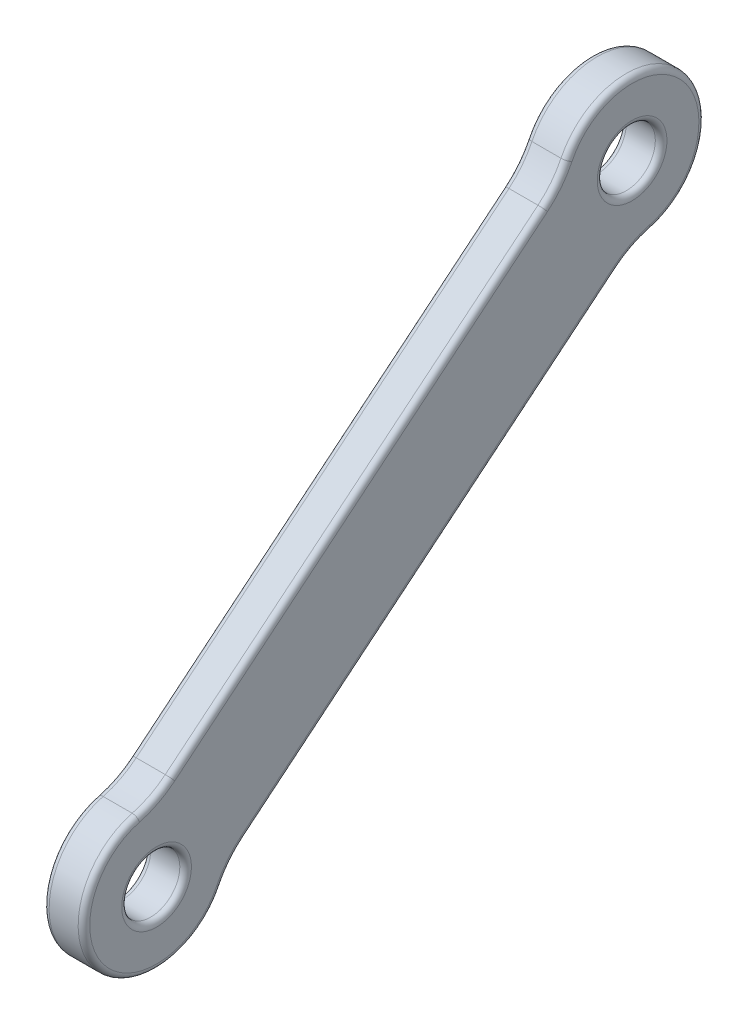
SolidWorks part; units mm, degrees
ref_plane "Front Plane" through (0, 0, 0) normal (1, 0, 0) x (0, 1, 0)
ref_plane "Top Plane" through (0, 0, 0) normal (0, 0, 1) x (0, 1, 0)
ref_plane "Right Plane" through (0, 0, 0) normal (0, 1, 0) x (-1, 0, 0)
sketch "Sketch1" plane through (0, 0, 0) normal (1, 0, 0) x (0, 1, 0)
  line L0 (-11.6048, -20) -> (24.9519, -20)
  line L1 (84.9519, 40) -> (84.9519, 57.8005)
  line L4 (-38.5328, 56.8878) -> (-47.7982, 43.6554)
  line L5 (64.9519, 37.5) -> (87.5414, -36.1119)
  line L6 (87.5414, -36.1119) -> (67.3498, -81.8536)
  line L7 (67.3498, -81.8536) -> (4.2234, -204.9062)
  line L8 (67.3498, -81.8536) -> (0, 0)
  line L9 (0, 0) -> (64.9519, 37.5) construction
  line L11 (-49.5322, 36.7009) -> (-46.3439, 10.7346)
  line L12 (-32.0778, 61.0001) -> (61.4789, 77.4967)
  arc A0 (24.9519, -20) -> (84.9519, 40) centre (24.9519, 40) ccw
  arc A1 (84.9519, 57.8005) -> (61.4789, 77.4967) centre (64.9519, 57.8005) ccw
  circle A3 centre (0, 0) radius 5
  circle A4 centre (0, 0) radius 10
  circle A5 centre (64.9519, 37.5) radius 5
  circle A6 centre (64.9519, 37.5) radius 10
  circle A7 centre (87.5414, -36.1119) radius 5
  circle A8 centre (87.5414, -36.1119) radius 10
  circle A9 centre (67.3498, -81.8536) radius 5
  circle A10 centre (67.3498, -81.8536) radius 10
  circle A11 centre (4.2234, -204.9062) radius 10
  circle A12 centre (4.2234, -204.9062) radius 50
  arc A13 (-46.3439, 10.7346) -> (-11.6048, -20) centre (-11.6048, 15) ccw
  arc A14 (-47.7982, 43.6554) -> (-49.5322, 36.7009) centre (-39.6067, 37.9196) ccw
  arc A16 (-32.0778, 61.0001) -> (-38.5328, 56.8878) centre (-30.3413, 51.152) ccw
  dimension "D3" = 60
  dimension "D16" = 20
  dimension "D17" = 10
  dimension "D18" = 20
  dimension "D19" = 100
  dimension "D22" = 35
  dimension "D24" = 10
  dimension "D7" = 10
  dimension "D1" = 20
  dimension "D4" = 20
  dimension "D5" = 95
  dimension "D9" = 10
  dimension "D10" = 75
  dimension "D11" = 77
  dimension "D12" = 50
  dimension "D13" = 138.3
  dimension "D14" = 3.34
  dimension "D15" = 30
  dimension "D20" = 106
sketch "Sketch2" plane through (0, 0, 0) normal (1, 0, 0) x (0, 1, 0)
  line L1 (67.7927, -66.6531) -> (15.0012, -2.493)
  line L2 (0, 0) -> (67.3498, -81.8536) construction
  line L3 (-0.4429, -15.2005) -> (52.3486, -79.3606)
  circle A0 centre (0, 0) radius 10 construction
  circle A1 centre (67.3498, -81.8536) radius 10 construction
  arc A2 (7.722, 6.3538) -> (-7.722, -6.3538) centre (0, 0) ccw construction
  arc A3 (59.6277, -88.2073) -> (59.0267, -87.3968) centre (67.3498, -81.8536) ccw construction
  circle A4 centre (0, 0) radius 5 construction
  circle A5 centre (67.3498, -81.8536) radius 5 construction
  circle A6 centre (0, 0) radius 5
  circle A7 centre (67.3498, -81.8536) radius 5
  arc A8 (12.0837, 3.1989) -> (-5.4663, -11.2414) centre (0, 0) ccw
  arc A9 (55.266, -85.0525) -> (72.8161, -70.6122) centre (67.3498, -81.8536) ccw
  arc A10 (67.7927, -66.6531) -> (72.8161, -70.6122) centre (79.3757, -57.1225) ccw
  arc A11 (12.0837, 3.1989) -> (15.0012, -2.493) centre (26.5842, 7.0377) ccw
  arc A14 (-5.4663, -11.2414) -> (-0.4429, -15.2005) centre (-12.026, -24.7311) cw
  arc A15 (52.3486, -79.3606) -> (55.266, -85.0525) centre (40.7655, -88.8913) cw
  dimension "D1" = 25
  dimension "D2" = 15
extrude "Boss-Extrude1" add sketch "Sketch2" along normal blind 7
fillet "Fillet1" radius 1 20 edges at (0, 67.3498, -86.8536) (0, 0, -5) (0, 41.3969, -34.573) (7, 67.3498, -86.8536) (7, 41.3969, -34.573) (7, 0, -5) (0, 13.2355, 0.1957) (0, -7.9422, 9.6525) (0, -2.7411, -12.9501) (0, 25.9529, -47.2805) (0, 54.1142, -82.0493) (0, 75.292, -91.5061) (0, 70.0909, -68.9035) (7, 75.292, -91.5061) (7, 54.1142, -82.0493) (7, 25.9529, -47.2805) (7, -2.7411, -12.9501) (7, -7.9422, 9.6525) (7, 13.2355, 0.1957) (7, 70.0909, -68.9035)
